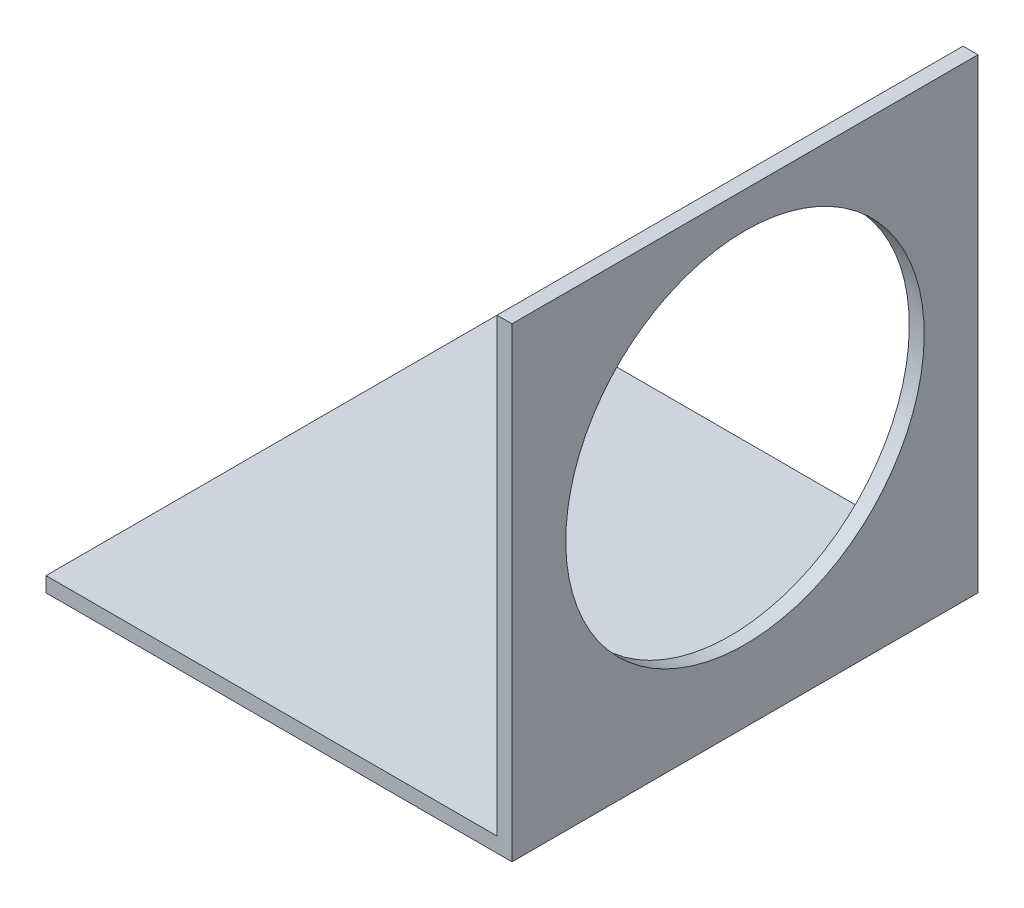
SolidWorks part; units mm, degrees
ref_plane "Front Plane" through (0, 0, 0) normal (0, 0, 1) x (1, 0, 0)
ref_plane "Top Plane" through (0, 0, 0) normal (0, 1, 0) x (1, 0, 0)
ref_plane "Right Plane" through (0, 0, 0) normal (1, 0, 0) x (0, 0, -1)
sketch "Sketch1" plane through (0, 0, 0) normal (0, 0, 1) x (1, 0, 0)
  line L0 (0, 0) -> (-95.885, 0)
  line L1 (-95.885, 0) -> (-95.885, -3.175)
  line L2 (-95.885, -3.175) -> (3.175, -3.175)
  line L3 (3.175, -3.175) -> (3.175, 95.885)
  line L4 (3.175, 95.885) -> (0, 95.885)
  line L5 (0, 95.885) -> (0, 0)
  dimension "D1" = 3.175
  dimension "D2" = 3.175
  dimension "D3" = 99.06
  dimension "D4" = 99.06
extrude "Boss-Extrude1" add sketch "Sketch1" along normal blind 99.06
sketch "Sketch2" plane through (3.175, 0, 0) normal (1, 0, 0) x (0, 0, -1)
  line L0 (-99.06, 46.355) -> (0, 46.355) construction
  line L1 (-99.06, -3.175) -> (-99.06, 95.885) construction
  line L2 (0, -3.175) -> (0, 95.885) construction
  line L3 (-49.53, -3.175) -> (-49.53, 50.165) construction
  line L4 (-99.06, -3.175) -> (0, -3.175) construction
  circle A0 centre (-49.53, 50.165) radius 38.1
  dimension "D1" = 76.2
  dimension "D2" = 53.34
extrude "Cut-Extrude1" cut sketch "Sketch2" against normal through all
